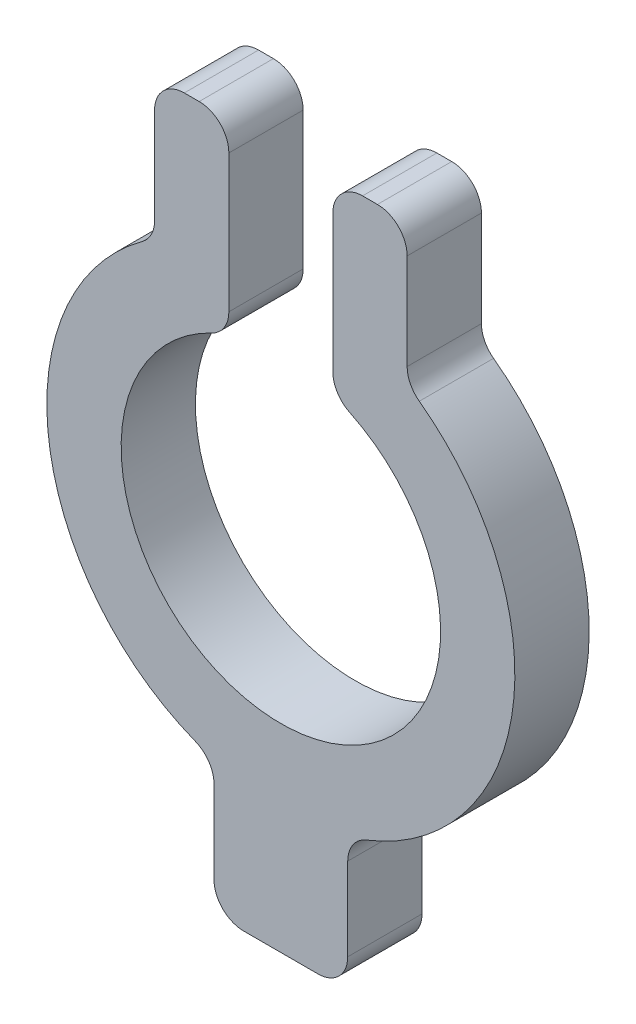
SolidWorks part; units mm, degrees
ref_plane "Front Plane" through (0, 0, 0) normal (0, 0, 1) x (1, 0, 0)
ref_plane "Top Plane" through (0, 0, 0) normal (0, 1, 0) x (1, 0, 0)
ref_plane "Right Plane" through (0, 0, 0) normal (1, 0, 0) x (0, 0, -1)
sketch "Sketch1" plane through (0, 0, 0) normal (0, 0, 1) x (1, 0, 0)
  line L0 (3.5, 22.7594) -> (8.5, 22.7594)
  line L2 (-3.5, 10.1643) -> (-3.5, 22.7594)
  line L4 (3.5, 10.1643) -> (3.5, 22.7594)
  line L5 (0, 0) -> (0, 8.507) construction
  line L8 (-8.5, 13.2594) -> (-8.5, 22.7594)
  line L9 (-8.5, 22.7594) -> (-3.5, 22.7594)
  line L10 (8.5, 13.2594) -> (8.5, 22.7594)
  line L11 (-4.5, -15.0935) -> (-4.5, -24.0935)
  line L12 (4.5, -15.0935) -> (4.5, -24.0935)
  line L13 (-4.5, -24.0935) -> (4.5, -24.0935)
  arc A0 (-3.5, 10.1643) -> (3.5, 10.1643) centre (0, 0) ccw
  arc A1 (-8.5, 13.2594) -> (-4.5, -15.0935) centre (0, 0) ccw
  arc A2 (4.5, -15.0935) -> (8.5, 13.2594) centre (0, 0) ccw
  point P4 (0, 15.75)
  point P9 (0, 15.75)
  dimension "D1" = 21.5
  dimension "D2" = 7
  dimension "D5" = 31.5
  dimension "D3" = 17
  dimension "D4" = 9.5
  dimension "D6" = 9
  dimension "D7" = 9
extrude "Boss-Extrude1" add sketch "Sketch1" along normal blind 5
fillet "Fillet1" radius 2 12 edges at (8.5, 22.7594, 2.5) (3.5, 22.7594, 2.5) (-3.5, 22.7594, 2.5) (-8.5, 22.7594, 2.5) (-8.5, 13.2594, 2.5) (3.5, 10.1643, 2.5) (-3.5, 10.1643, 2.5) (-4.5, -24.0935, 2.5) (-4.5, -15.0935, 2.5) (4.5, -24.0935, 2.5) (4.5, -15.0935, 2.5) (8.5, 13.2594, 2.5)
